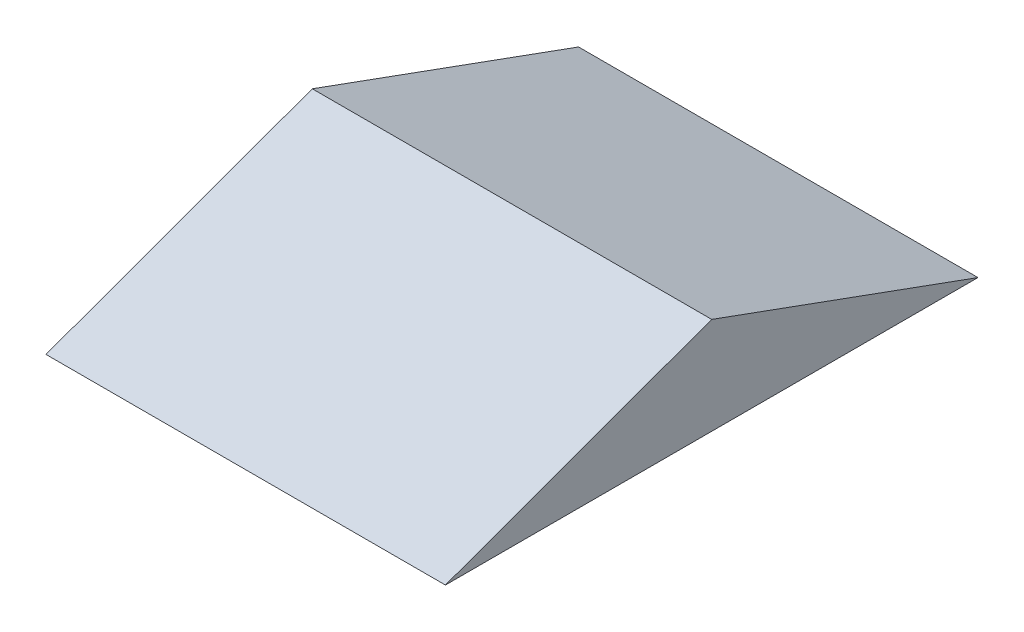
SolidWorks part; units mm, degrees
ref_plane "Спереди" through (0, 0, 0) normal (0, 0, 1) x (1, 0, 0)
ref_plane "Сверху" through (0, 0, 0) normal (0, 1, 0) x (1, 0, 0)
ref_plane "Справа" through (0, 0, 0) normal (1, 0, 0) x (0, 0, -1)
sketch "Эскиз1" plane through (0, 0, 0) normal (1, 0, 0) x (0, 0, -1)
  line L0 (-100, 0) -> (100, 0)
  line L1 (-100, 0) -> (0, 36.397)
  line L2 (0, 36.397) -> (100, 0)
  line L3 (0, 51.3138) -> (0, -11.1283) construction
  dimension "D1" = 200
  dimension "D2" = 20
extrude "Бобышка-Вытянуть1" add sketch "Эскиз1" along normal mid plane 150
